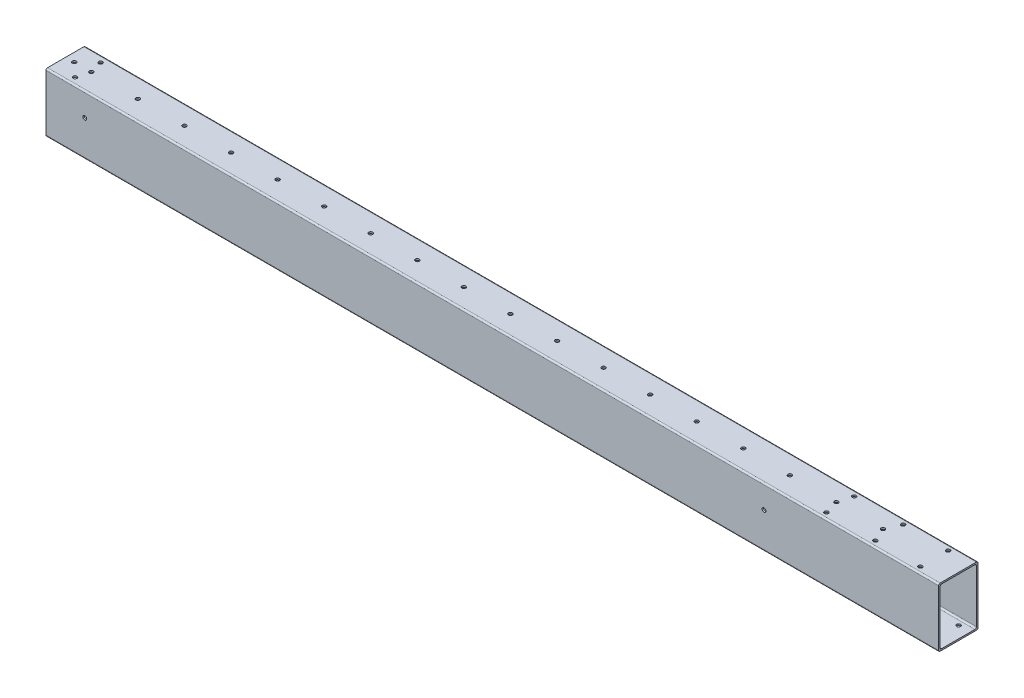
SolidWorks part; units mm, degrees
material "A500"
ref_plane "Alzado" through (0, 0, 0) normal (0, 0, 1) x (1, 0, 0)
ref_plane "Planta" through (0, 0, 0) normal (0, 1, 0) x (1, 0, 0)
ref_plane "Vista lateral" through (0, 0, 0) normal (1, 0, 0) x (0, 0, -1)
sketch "Sketch1" plane through (0, 0, 0) normal (1, 0, 0) x (0, 0, -1)
  line L1 (25.4, 38.1) -> (-25.4, 38.1)
  line L2 (25.4, 38.1) -> (25.4, -38.1)
  line L3 (25.4, -38.1) -> (-25.4, -38.1)
  line L4 (-25.4, 38.1) -> (-25.4, -38.1)
  line L5 (25.4, 38.1) -> (-25.4, -38.1) construction
  line L6 (25.4, -38.1) -> (-25.4, 38.1) construction
  point P0 (0, 0)
  dimension "D1" = 76.2
  dimension "D2" = 50.8
extrude "Boss-Extrude1" add sketch "Sketch1" against normal blind 1150
sketch "Sketch2" plane through (0, 0, 0) normal (1, 0, 0) x (0, 0, -1)
  line L0 (25.4, 38.1) -> (-25.4, 38.1) construction
  line L1 (23.4, 36.1) -> (-23.4, 36.1)
  line L2 (23.4, 36.1) -> (23.4, -36.1)
  line L3 (23.4, -36.1) -> (-23.4, -36.1)
  line L4 (-23.4, 36.1) -> (-23.4, -36.1)
  line L5 (23.4, 36.1) -> (-23.4, -36.1) construction
  line L6 (23.4, -36.1) -> (-23.4, 36.1) construction
  line L7 (25.4, -38.1) -> (25.4, 38.1) construction
  point P0 (0, 0)
  dimension "D1" = 2
  dimension "D2" = 2
extrude "Cut-Extrude1" cut sketch "Sketch2" against normal through all
fillet "Fillet2" radius 2 8 edges at (-575, -38.1, -25.4) (-575, -38.1, 25.4) (-575, 38.1, 25.4) (-575, 38.1, -25.4) (-575, -36.1, -23.4) (-575, 36.1, -23.4) (-575, -36.1, 23.4) (-575, 36.1, 23.4)
sketch "Croquis1" plane through (0, -38.1, 0) normal (0, -1, 0) x (1, 0, 0)
  line L0 (-76.2, 25.4) -> (-76.2, -25.4) construction
  line L1 (-1150, 25.4) -> (0, 25.4) construction
  line L2 (0, -25.4) -> (-1150, -25.4) construction
  line L3 (0, 23.4) -> (0, -23.4) construction
  line L4 (0, 15.4) -> (-76.2, 15.4) construction
  line L5 (0, -15.4) -> (-76.2, -15.4) construction
  line L6 (-76.2, 0) -> (0, 0) construction
  circle A0 centre (-38.1, 0) radius 2.5
  circle A1 centre (-61.2, 15.4) radius 2.5
  circle A2 centre (-15, 15.4) radius 2.5
  circle A3 centre (-15, -15.4) radius 2.5
  circle A4 centre (-61.2, -15.4) radius 2.5
  dimension "D8" = 5
  dimension "D9" = 5
  dimension "D10" = 5
  dimension "D11" = 5
  dimension "D12" = 5
  dimension "D1" = 76.2
  dimension "D2" = 10
  dimension "D3" = 10
  dimension "D4" = 15
  dimension "D5" = 15
  dimension "D6" = 15
  dimension "D7" = 15
extrude "Cortar-Extruir1" cut sketch "Croquis1" against normal blind 5
pattern_linear "MatrizL1" count 4 spacing 357.9333 along (-1, 0, 0) of "Cortar-Extruir1"
sketch "Croquis2" plane through (0, 0, 25.4) normal (0, 0, 1) x (1, 0, 0)
  line L0 (0, 8.1) -> (-1150, 8.1) construction
  line L1 (0, 36.1) -> (0, -36.1) construction
  line L2 (-1150, 36.1) -> (-1150, -36.1) construction
  line L3 (-1150, 38.1) -> (0, 38.1) construction
  circle A0 centre (-225, 8.1) radius 2.5
  circle A1 centre (-1100, 8.1) radius 2.5
  dimension "D2" = 5
  dimension "D3" = 5
  dimension "D1" = 30
  dimension "D4" = 225
  dimension "D5" = 50
extrude "Cortar-Extruir2" cut sketch "Croquis2" against normal blind 10
sketch "Croquis3" plane through (0, 38.1, 0) normal (0, 1, 0) x (1, 0, 0)
  line L0 (0, 17.9) -> (-152, 17.9) construction
  line L1 (0, 23.4) -> (0, -23.4) construction
  line L2 (-152, 17.9) -> (-152, -17.9) construction
  line L3 (-152, -17.9) -> (0, -17.9) construction
  line L4 (-1150, 25.4) -> (0, 25.4) construction
  line L5 (0, -25.4) -> (-1150, -25.4) construction
  circle A0 centre (-152, 17.9) radius 2.5
  circle A1 centre (-152, -17.9) radius 2.5
  circle A2 centre (-89, -17.9) radius 2.5
  circle A3 centre (-89, 17.9) radius 2.5
  circle A4 centre (-31, 17.9) radius 2.5
  circle A5 centre (-31, -17.9) radius 2.5
  dimension "D8" = 5
  dimension "D9" = 5
  dimension "D10" = 5
  dimension "D11" = 5
  dimension "D12" = 5
  dimension "D13" = 5
  dimension "D1" = 152
  dimension "D2" = 7.5
  dimension "D3" = 7.5
  dimension "D4" = 31
  dimension "D5" = 58
  dimension "D6" = 31
  dimension "D7" = 58
extrude "Cortar-Extruir3" cut sketch "Croquis3" against normal blind 10
sketch "Croquis4" plane through (0, 38.1, 0) normal (0, 1, 0) x (1, 0, 0)
  line L0 (-1150, 0) -> (0, 0) construction
  line L1 (-1150, 23.4) -> (-1150, -23.4) construction
  circle A0 centre (-1117, 0) radius 2.5
  dimension "D2" = 5
  dimension "D1" = 33
extrude "Cortar-Extruir4" cut sketch "Croquis4" against normal blind 10
pattern_linear "MatrizL2" count 18 spacing 60 along (1, 0, 0) of "Cortar-Extruir4"
sketch "Croquis5" plane through (0, 38.1, 0) normal (0, 1, 0) x (1, 0, 0)
  line L0 (-1121.5, 25.4) -> (-1121.5, -25.4) construction
  line L1 (-1150, 25.4) -> (0, 25.4) construction
  line L2 (0, -25.4) -> (-1150, -25.4) construction
  line L3 (-1150, 23.4) -> (-1150, -23.4) construction
  line L4 (-1121.5, 0) -> (-1150, 0) construction
  circle A0 centre (-1121.5, 16.4) radius 2.5
  circle A1 centre (-1121.5, -16.4) radius 2.5
  circle A2 centre (-1139, 0) radius 2.5
  dimension "D5" = 5
  dimension "D6" = 5
  dimension "D7" = 5
  dimension "D1" = 28.5
  dimension "D2" = 16.4
  dimension "D3" = 16.4
  dimension "D4" = 11
extrude "Cortar-Extruir5" cut sketch "Croquis5" against normal blind 10
